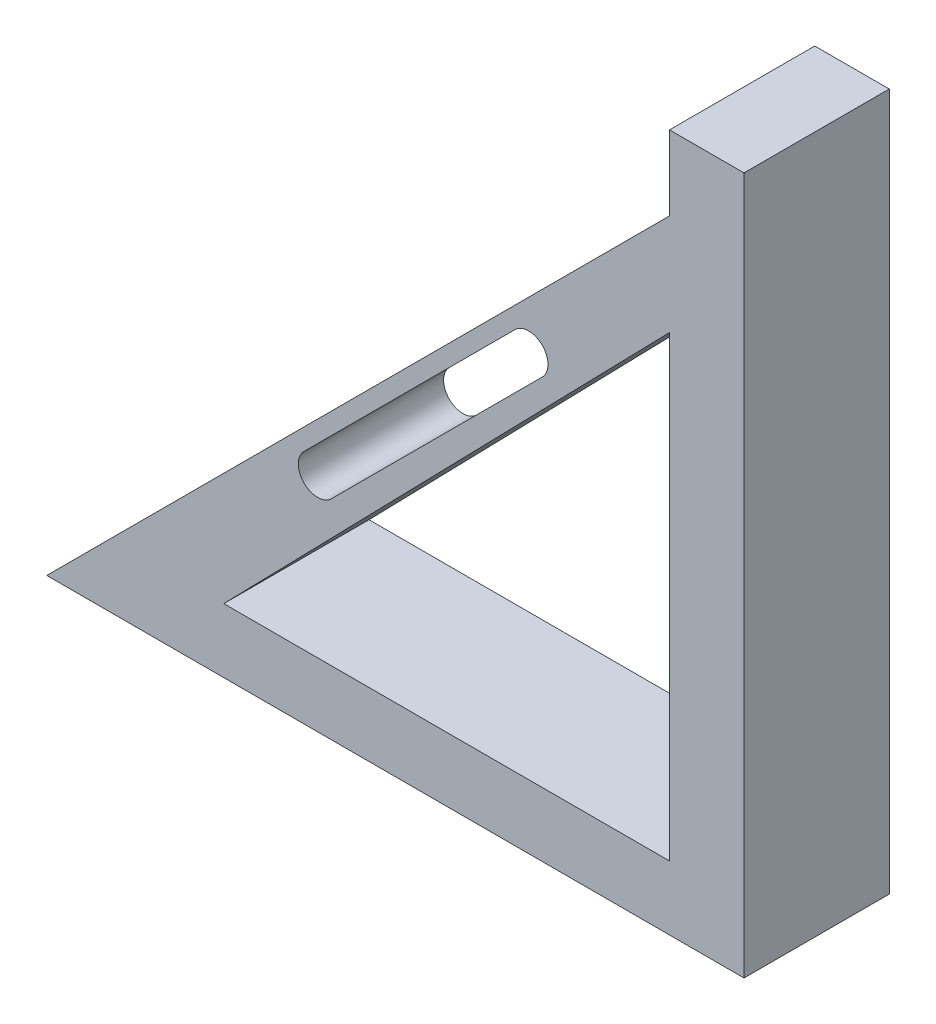
SolidWorks part; units mm, degrees
material "Cedar"
ref_plane "Front" through (0, 0, 0) normal (0, 0, 1) x (1, 0, 0)
ref_plane "Top" through (0, 0, 0) normal (0, 1, 0) x (1, 0, 0)
ref_plane "Right" through (0, 0, 0) normal (1, 0, 0) x (0, 0, -1)
sketch "Sketch1" plane through (0, 0, 0) normal (0, 0, 1) x (1, 0, 0)
  line L0 (47.177, 107.177) -> (-60, 0)
  line L1 (47.177, 89.7893) -> (47.177, 11.0331)
  line L2 (47.177, 89.7893) -> (-29.5336, 11.0331)
  line L3 (-60, 0) -> (60, 0)
  line L4 (60, 120) -> (60, 0)
  line L5 (-29.5336, 11.0331) -> (47.177, 11.0331)
  line L6 (47.177, 107.177) -> (47.177, 120)
  line L7 (47.177, 120) -> (60, 120)
  point P4 (0, 60)
  dimension "D1" = 120
  dimension "D2" = 120
  dimension "D5" = 12.823
extrude "Boss-Extrude1" add sketch "Sketch1" along normal blind 25
sketch "Sketch2" plane through (0, 0, 25) normal (0, 0, 1) x (1, 0, 0)
  line L0 (22.9411, 74.5825) -> (-13.3759, 38.2656) construction
  line L1 (25.2945, 72.2291) -> (-11.0224, 35.9122)
  line L2 (20.5876, 76.936) -> (-15.7293, 40.6191)
  arc A0 (25.2945, 72.2291) -> (20.5876, 76.936) centre (22.9411, 74.5825) ccw
  arc A1 (-15.7293, 40.6191) -> (-11.0224, 35.9122) centre (-13.3759, 38.2656) ccw
  point P2 (4.7826, 56.4241)
extrude "Cut-Extrude1" cut sketch "Sketch2" against normal blind 25
